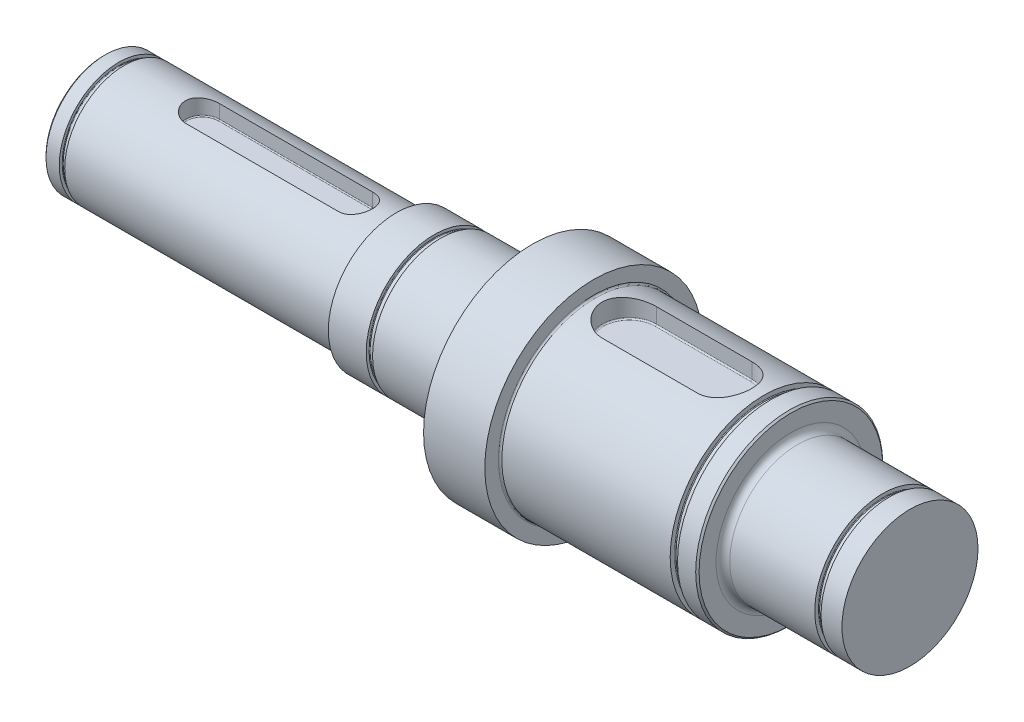
SolidWorks part; units mm, degrees
ref_plane "Front Plane" through (0, 0, 0) normal (0, 0, 1) x (1, 0, 0)
ref_plane "Top Plane" through (0, 0, 0) normal (0, 1, 0) x (1, 0, 0)
ref_plane "Right Plane" through (0, 0, 0) normal (1, 0, 0) x (0, 0, -1)
sketch "Sketch1" plane through (0, 0, 0) normal (1, 0, 0) x (0, 0, -1)
  circle A0 centre (0, 0) radius 32
  dimension "D1" = 64
extrude "Boss-Extrude1" add sketch "Sketch1" along normal mid plane 224
sketch "Sketch2" plane through (-112, 0, 0) normal (-1, 0, 0) x (0, 0, 1)
  circle A0 centre (0, 0) radius 17.5
  circle A1 centre (0, 0) radius 32 construction
  circle A2 centre (0, 0) radius 32
  dimension "D1" = 35
extrude "Cut-Extrude1" cut sketch "Sketch2" against normal blind 86
sketch "Sketch3" plane through (-26, 0, 0) normal (-1, 0, 0) x (0, 0, 1)
  circle A0 centre (0, 0) radius 20
  circle A1 centre (0, 0) radius 32 construction
  circle A2 centre (0, 0) radius 32
  dimension "D1" = 40
extrude "Cut-Extrude2" cut sketch "Sketch3" against normal blind 32
sketch "Sketch4" plane through (112, 0, 0) normal (1, 0, 0) x (0, 0, -1)
  circle A0 centre (0, 0) radius 20
  circle A1 centre (0, 0) radius 32 construction
  circle A2 centre (0, 0) radius 32
  dimension "D1" = 40
extrude "Cut-Extrude3" cut sketch "Sketch4" against normal blind 30
sketch "Sketch5" plane through (82, 0, 0) normal (1, 0, 0) x (0, 0, -1)
  circle A0 centre (0, 0) radius 27.5
  circle A1 centre (0, 0) radius 32 construction
  circle A2 centre (0, 0) radius 32
  dimension "D1" = 55
extrude "Cut-Extrude4" cut sketch "Sketch5" against normal blind 58
fillet "Fillet1" radius 2 2 edges at (82, 0, -20) (6, 0, 20)
sketch "Sketch7" plane through (0, 0, 0) normal (0, 0, 1) x (1, 0, 0)
  line L0 (6, 32) -> (6, -32) construction
  line L1 (-22.85, 22.3194) -> (-21, 22.3194)
  line L2 (-22.85, 22.3194) -> (-22.85, 19)
  line L3 (-22.85, 19) -> (-21, 19)
  line L4 (-21, 22.3194) -> (-21, 19)
  line L5 (4, 20) -> (-26, 20) construction
  line L6 (-21.6986, 0) -> (-24.85, 0) construction
  dimension "D1" = 27
  dimension "D2" = 1.85
  dimension "D3" = 1
revolve "Cut-Revolve2" cut sketch "Sketch7" angle 360 about L6
fillet "Fillet4" radius 0.175 2 edges at (-22.85, 0, -19) (-21, 0, -19)
sketch "Sketch8" plane through (0, 0, 0) normal (0, 0, 1) x (1, 0, 0)
  line L0 (24, -32) -> (24, 32) construction
  line L1 (74, 30.1351) -> (76.15, 30.1351)
  line L2 (74, 30.1351) -> (74, 26)
  line L3 (74, 26) -> (76.15, 26)
  line L4 (76.15, 30.1351) -> (76.15, 26)
  line L5 (82, 27.5) -> (24, 27.5) construction
  line L6 (71.1978, 0) -> (72.5142, 0) construction
  dimension "D1" = 50
  dimension "D2" = 2.15
  dimension "D3" = 1.5
revolve "Cut-Revolve3" cut sketch "Sketch8" angle 360 about L6
fillet "Fillet5" radius 0.2 2 edges at (74, 0, 26) (76.15, 0, 26)
sketch "Sketch9" plane through (0, 0, 0) normal (0, 0, 1) x (1, 0, 0)
  line L0 (82, -27.5) -> (82, 27.5) construction
  line L1 (109, 21.803) -> (110.85, 21.803)
  line L2 (109, 21.803) -> (109, 18.75)
  line L3 (109, 18.75) -> (110.85, 18.75)
  line L4 (110.85, 21.803) -> (110.85, 18.75)
  line L5 (112, 20) -> (84, 20) construction
  line L6 (107.7004, 0) -> (119.5577, 0) construction
  dimension "D1" = 27
  dimension "D2" = 1.85
  dimension "D3" = 1.25
revolve "Cut-Revolve4" cut sketch "Sketch9" angle 360 about L6
fillet "Fillet6" radius 0.175 2 edges at (109, 0, 18.75) (110.85, 0, 18.75)
sketch "Sketch10" plane through (112, 0, 0) normal (1, 0, 0) x (0, 0, -1)
  circle A0 centre (0, 0) radius 20 construction
  circle A1 centre (0, 0) radius 20
extrude "Boss-Extrude2" add sketch "Sketch10" along normal blind 5
sketch "Sketch12" plane through (0, 0, 0) normal (0, 1, 0) x (1, 0, 0)
  line L0 (-26, 20) -> (-26, -20) construction
  line L1 (-46, -5) -> (-91, -5)
  line L3 (-46, 5) -> (-91, 5)
  line L5 (-46, -5) -> (-91, 5) construction
  line L6 (-46, 5) -> (-91, -5) construction
  arc A0 (-91, 5) -> (-91, -5) centre (-91, 0) ccw
  arc A1 (-46, 5) -> (-46, -5) centre (-46, 0) cw
  point P0 (-68.5, 0)
  dimension "D1" = 45
  dimension "D2" = 10
  dimension "D3" = 20
  dimension "D4" = 0
extrude "Cut-Extrude6" cut sketch "Sketch12" along normal up to surface (4.2705 mm away) from offset 12.5
fillet "Fillet8" radius 0.3 4 edges at (-68.5, 12.5, -5) (-41, 12.5, 0) (-68.5, 12.5, 5) (-96, 12.5, 0)
sketch "Sketch13" plane through (0, 0, 0) normal (0, 1, 0) x (1, 0, 0)
  line L0 (24, -32) -> (24, 32) construction
  line L1 (34.5, -8) -> (62.5, -8)
  line L3 (34.5, 8) -> (62.5, 8)
  line L5 (34.5, -8) -> (62.5, 8) construction
  line L6 (34.5, 8) -> (62.5, -8) construction
  arc A0 (34.5, 8) -> (34.5, -8) centre (34.5, 0) ccw
  arc A1 (62.5, 8) -> (62.5, -8) centre (62.5, 0) cw
  point P0 (48.5, 0)
  dimension "D3" = 10.5
  dimension "D1" = 28
  dimension "D2" = 16
  dimension "D4" = 0
extrude "Cut-Extrude7" cut sketch "Sketch13" along normal up to surface (4.8106 mm away) from offset 21.5
fillet "Fillet9" radius 0.4 4 edges at (48.5, 21.5, 8) (26.5, 21.5, 0) (48.5, 21.5, -8) (70.5, 21.5, 0)
sketch "Sketch14" plane through (-26, 0, 0) normal (-1, 0, 0) x (0, 0, 1)
  circle A1 centre (0, 0) radius 20
  circle A2 centre (0, 0) radius 20
  dimension "D1" = 0
extrude "Boss-Extrude3" add sketch "Sketch14" along normal blind 8
sketch "Sketch15" plane through (-112, 0, 0) normal (-1, 0, 0) x (0, 0, 1)
  circle A1 centre (0, 0) radius 17.5
  circle A2 centre (0, 0) radius 17.5
  dimension "D1" = 0
extrude "Boss-Extrude4" add sketch "Sketch15" along normal blind 8
sketch "Sketch16" plane through (0, 0, 0) normal (0, 0, 1) x (1, 0, 0)
  line L0 (-34, 20) -> (-34, -20) construction
  line L1 (-115.6, 19.2052) -> (-114, 19.2052)
  line L2 (-115.6, 19.2052) -> (-115.6, 16.5)
  line L3 (-115.6, 16.5) -> (-114, 16.5)
  line L4 (-114, 19.2052) -> (-114, 16.5)
  line L5 (-96, 17.5) -> (-120, 17.5) construction
  line L6 (-114, 0) -> (-108.3489, 0) construction
  dimension "D1" = 80
  dimension "D2" = 1.6
  dimension "D3" = 1
revolve "Cut-Revolve5" cut sketch "Sketch16" angle 360 about L6
fillet "Fillet10" radius 0.15 2 edges at (-115.6, 0, 16.5) (-114, 0, 16.5)
chamfer "Chamfer1" distance 0.5 angle 45 2 edges at (-120, 0, 17.5) (82, 0, -27.5)
fillet "Fillet11" radius 1 1 edges at (-34, 0, 17.5)
fillet "Fillet12" radius 0.5 1 edges at (24, 0, -27.5)
